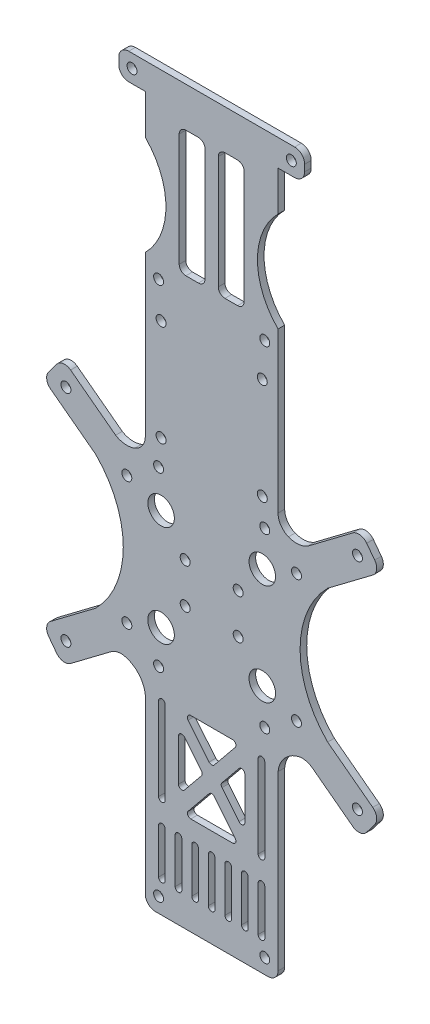
SolidWorks part; units mm, degrees
material "Thornel Mat VMA"
ref_plane "Alzado" through (0, 0, 0) normal (0, 0, 1) x (1, 0, 0)
ref_plane "Planta" through (0, 0, 0) normal (0, 1, 0) x (1, 0, 0)
ref_plane "Vista lateral" through (0, 0, 0) normal (1, 0, 0) x (0, 0, -1)
sketch "Croquis1" plane through (0, 0, 0) normal (0, 0, 1) x (1, 0, 0)
  line L0 (0, 0) -> (0, 130.25) construction
  line L1 (-15.25, 15.25) -> (15.25, 15.25) construction
  line L2 (-15.25, 15.25) -> (-15.25, -15.25) construction
  line L3 (-15.25, -15.25) -> (15.25, -15.25) construction
  line L4 (15.25, 15.25) -> (15.25, -15.25) construction
  line L5 (-15.25, 15.25) -> (15.25, -15.25) construction
  line L6 (-15.25, -15.25) -> (15.25, 15.25) construction
  line L7 (0, 0) -> (0, -90.25) construction
  line L8 (20, 130.25) -> (-20, 130.25)
  line L9 (-20, 130.25) -> (-20, 30.25)
  line L10 (20, -90.25) -> (-20, -90.25)
  line L11 (-20, -90.25) -> (-20, -35.25)
  line L12 (0, 0) -> (-127.7817, 96.2904) construction
  line L13 (0, 0) -> (-127.7817, -96.2904) construction
  line L14 (0, 0) -> (-160, 0) construction
  line L15 (-47.9181, 36.1089) -> (-50.9272, 32.1157)
  line L16 (-47.9181, 36.1089) -> (-44.9091, 40.1021)
  line L17 (-44.9091, 40.1021) -> (-28.9363, 28.0658)
  line L18 (-50.9272, 32.1157) -> (-34.9545, 20.0794)
  line L19 (-47.9181, -36.1089) -> (-50.9272, -32.1157)
  line L20 (-47.9181, -36.1089) -> (-44.9091, -40.1021)
  line L21 (-50.9272, -32.1157) -> (-34.9545, -20.0794)
  line L22 (-44.9091, -40.1021) -> (-28.9363, -28.0658)
  line L23 (20, -90.25) -> (20, -35.25)
  line L24 (44.9091, -40.1021) -> (28.9363, -28.0658)
  line L25 (47.9181, -36.1089) -> (44.9091, -40.1021)
  line L26 (47.9181, -36.1089) -> (50.9272, -32.1157)
  line L27 (50.9272, -32.1157) -> (34.9545, -20.0794)
  line L28 (50.9272, 32.1157) -> (34.9545, 20.0794)
  line L29 (47.9181, 36.1089) -> (50.9272, 32.1157)
  line L30 (47.9181, 36.1089) -> (44.9091, 40.1021)
  line L31 (44.9091, 40.1021) -> (28.9363, 28.0658)
  line L32 (20, 130.25) -> (20, 30.25)
  line L33 (-11, -67.25) -> (-11, -80.75)
  line L35 (-16, -67.25) -> (-16, -80.75)
  line L37 (-14, -67.25) -> (-14, -80.75)
  line L38 (-9, -67.25) -> (-9, -80.75)
  line L39 (-6, -67.25) -> (-6, -80.75)
  line L40 (-4, -67.25) -> (-4, -80.75)
  line L41 (-1, -67.25) -> (-1, -80.75)
  line L42 (1, -67.25) -> (1, -80.75)
  line L43 (4, -67.25) -> (4, -80.75)
  line L44 (6, -67.25) -> (6, -80.75)
  line L45 (9, -67.25) -> (9, -80.75)
  line L46 (11, -67.25) -> (11, -80.75)
  line L47 (14, -67.25) -> (14, -80.75)
  line L48 (16, -67.25) -> (16, -80.75)
  line L91 (-11, 62.75) -> (-11, 49.25) [skipped]
  line L92 (-9, 62.75) -> (-9, 49.25) [skipped]
  line L93 (-6, 62.75) -> (-6, 49.25) [skipped]
  line L94 (-4, 62.75) -> (-4, 49.25) [skipped]
  line L95 (-1, 62.75) -> (-1, 49.25) [skipped]
  line L96 (1, 62.75) -> (1, 49.25) [skipped]
  line L97 (4, 62.75) -> (4, 49.25) [skipped]
  line L98 (6, 62.75) -> (6, 49.25) [skipped]
  line L99 (9, 62.75) -> (9, 49.25) [skipped]
  line L100 (11, 62.75) -> (11, 49.25) [skipped]
  line L101 (14, 62.75) -> (14, 49.25) [skipped]
  line L102 (16, 62.75) -> (16, 49.25) [skipped]
  line L103 (-16, 62.75) -> (-16, 49.25) [skipped]
  line L104 (-14, 62.75) -> (-14, 49.25) [skipped]
  line L105 (14, -34.75) -> (14, -59.75)
  line L107 (-16, -34.75) -> (-16, -59.75)
  line L109 (-14, -34.75) -> (-14, -59.75)
  line L110 (16, -34.75) -> (16, -59.75)
  line L111 (-20, 130.25) -> (-10, 130.25) construction
  circle A0 centre (-15.25, 15.25) radius 4
  circle A1 centre (-15.25, -15.25) radius 4
  circle A2 centre (0, 0) radius 160 construction
  circle A4 centre (-127.7817, 96.2904) radius 90 construction
  circle A5 centre (-127.7817, -96.2904) radius 90 construction
  arc A6 (-28.9363, 28.0658) -> (-20, 30.25) centre (-25.5603, 33.6261) ccw
  arc A7 (-34.9545, 20.0794) -> (-34.9545, -20.0794) centre (-55.0339, 0) cw
  arc A8 (-28.9363, -28.0658) -> (-20, -35.25) centre (-28.0603, -36.1261) cw
  circle A9 centre (15.25, -15.25) radius 4
  arc A10 (28.9363, -28.0658) -> (20, -35.25) centre (28.0603, -36.1261) ccw
  circle A11 centre (15.25, 15.25) radius 4
  arc A12 (34.9545, 20.0794) -> (34.9545, -20.0794) centre (55.0339, 0) ccw
  arc A13 (28.9363, 28.0658) -> (20, 30.25) centre (25.5603, 33.6261) cw
  circle A14 centre (-43.925, 33.0998) radius 1.5
  circle A15 centre (-43.925, -33.0998) radius 1.5
  circle A16 centre (43.925, -33.0998) radius 1.5
  circle A17 centre (43.925, 33.0998) radius 1.5
  circle A23 centre (-7.9864, 6.0182) radius 1.5
  circle A24 centre (-25.5603, 19.2611) radius 1.5
  circle A25 centre (-25.5603, -19.2611) radius 1.5
  circle A26 centre (-7.9864, -6.0182) radius 1.5
  circle A27 centre (25.5603, -19.2611) radius 1.5
  circle A28 centre (7.9864, -6.0182) radius 1.5
  circle A29 centre (7.9864, 6.0182) radius 1.5
  circle A30 centre (25.5603, 19.2611) radius 1.5
  circle A31 centre (-16, -85.75) radius 1.5
  circle A32 centre (-16, -25.75) radius 1.5
  circle A33 centre (-16, 26.25) radius 1.5
  circle A34 centre (-16, 75.25) radius 1.5
  circle A35 centre (16, -85.75) radius 1.5
  circle A36 centre (16, -25.75) radius 1.5
  circle A37 centre (16, 26.25) radius 1.5
  circle A38 centre (16, 75.25) radius 1.5
  arc A39 (-16, -67.25) -> (-14, -67.25) centre (-15, -67.25) cw
  arc A40 (-16, -80.75) -> (-14, -80.75) centre (-15, -80.75) ccw
  arc A41 (-11, -80.75) -> (-9, -80.75) centre (-10, -80.75) ccw
  arc A42 (-11, -67.25) -> (-9, -67.25) centre (-10, -67.25) cw
  arc A43 (-6, -80.75) -> (-4, -80.75) centre (-5, -80.75) ccw
  arc A44 (-6, -67.25) -> (-4, -67.25) centre (-5, -67.25) cw
  arc A45 (-1, -80.75) -> (1, -80.75) centre (0, -80.75) ccw
  arc A46 (-1, -67.25) -> (1, -67.25) centre (0, -67.25) cw
  arc A47 (4, -80.75) -> (6, -80.75) centre (5, -80.75) ccw
  arc A48 (4, -67.25) -> (6, -67.25) centre (5, -67.25) cw
  arc A49 (9, -80.75) -> (11, -80.75) centre (10, -80.75) ccw
  arc A50 (9, -67.25) -> (11, -67.25) centre (10, -67.25) cw
  arc A51 (14, -80.75) -> (16, -80.75) centre (15, -80.75) ccw
  arc A52 (14, -67.25) -> (16, -67.25) centre (15, -67.25) cw
  arc A95 (-11, 49.25) -> (-9, 49.25) centre (-10, 49.25) ccw [skipped]
  arc A96 (-11, 62.75) -> (-9, 62.75) centre (-10, 62.75) cw [skipped]
  arc A97 (-6, 49.25) -> (-4, 49.25) centre (-5, 49.25) ccw [skipped]
  arc A98 (-6, 62.75) -> (-4, 62.75) centre (-5, 62.75) cw [skipped]
  arc A99 (-1, 49.25) -> (1, 49.25) centre (0, 49.25) ccw [skipped]
  arc A100 (-1, 62.75) -> (1, 62.75) centre (0, 62.75) cw [skipped]
  arc A101 (4, 49.25) -> (6, 49.25) centre (5, 49.25) ccw [skipped]
  arc A102 (4, 62.75) -> (6, 62.75) centre (5, 62.75) cw [skipped]
  arc A103 (9, 49.25) -> (11, 49.25) centre (10, 49.25) ccw [skipped]
  arc A104 (9, 62.75) -> (11, 62.75) centre (10, 62.75) cw [skipped]
  arc A105 (14, 49.25) -> (16, 49.25) centre (15, 49.25) ccw [skipped]
  arc A106 (14, 62.75) -> (16, 62.75) centre (15, 62.75) cw [skipped]
  arc A107 (-16, 49.25) -> (-14, 49.25) centre (-15, 49.25) ccw [skipped]
  arc A108 (-16, 62.75) -> (-14, 62.75) centre (-15, 62.75) cw [skipped]
  circle A109 centre (-15.25, 64.75) radius 1.5
  circle A110 centre (15.25, 64.75) radius 1.5
  circle A111 centre (15.25, 34.25) radius 1.5
  circle A112 centre (-15.25, 34.25) radius 1.5
  arc A113 (-16, -34.75) -> (-14, -34.75) centre (-15, -34.75) cw
  arc A114 (-16, -59.75) -> (-14, -59.75) centre (-15, -59.75) ccw
  arc A115 (16, -59.75) -> (14, -59.75) centre (15, -59.75) cw
  arc A116 (16, -34.75) -> (14, -34.75) centre (15, -34.75) ccw
  point P1 (0, 0)
  dimension "D2" = 130.25
  dimension "D8" = 30.5
  dimension "D9" = 180
  dimension "D10" = 320
  dimension "D13" = 180
  dimension "D20" = 5
  dimension "D21" = 5
  dimension "D22" = 8
  dimension "D23" = 8
  dimension "D24" = 9.5
  dimension "D25" = 8
  dimension "D26" = 4.75
  dimension "D28" = 10
  dimension "D29" = 16
  dimension "D31" = 16
  dimension "D33" = 3
  dimension "D34" = 16
  dimension "D36" = 4.75
  dimension "D41" = 8.1078
  dimension "D27" = 6.505
  dimension "D32" = 20
  dimension "D1" = 30.5
  dimension "D4" = 20
  dimension "D5" = 13.5
  dimension "D6" = 20
  dimension "D7" = 10
  dimension "D11" = 37
  dimension "D12" = 37
  dimension "D14" = 60
  dimension "D15" = 5
  dimension "D16" = 5
  dimension "D17" = 20
  dimension "D18" = 60
  dimension "D19" = 5
  dimension "D30" = 4.5
  dimension "D35" = 11
  dimension "D37" = 5
  dimension "D38" = 2
  dimension "D39" = 4
  dimension "D40" = 55
  dimension "D42" = 25
  dimension "D43" = 9
  dimension "D46" = 55
  dimension "D47" = 4
  dimension "D49" = 2
  dimension "D44" = 7
  dimension "D45" = 2
extrude "Saliente-Extruir1" add sketch "Croquis1" along normal blind 2
sketch "Croquis2" plane through (0, 0, 2) normal (0, 0, 1) x (1, 0, 0)
  line L0 (-28.9363, 28.0658) -> (-44.9091, 40.1021)
  line L1 (-44.9091, 40.1021) -> (-50.9272, 32.1157)
  line L2 (-50.9272, 32.1157) -> (-34.9545, 20.0794)
  circle A0 centre (-43.925, 33.0998) radius 1.5
  circle A1 centre (-25.5603, 19.2611) radius 1.5
  circle A2 centre (-15.25, 15.25) radius 4
  circle A3 centre (-7.9864, 6.0182) radius 1.5
  circle A4 centre (-16, 26.25) radius 1.5
  circle A5 centre (0, 0) radius 10
fillet "Redondeo2" radius 3 10 edges at (50.9272, -32.1157, 1) (44.9091, -40.1021, 1) (50.9272, 32.1157, 1) (44.9091, 40.1021, 1) (-44.9091, 40.1021, 1) (-50.9272, 32.1157, 1) (-50.9272, -32.1157, 1) (-44.9091, -40.1021, 1) (20, -90.25, 1) (-20, -90.25, 1)
fillet "Redondeo3" radius 5 4 edges at (20, 30.25, 1) (-20, 30.25, 1) (28.9363, -28.0658, 1) (-28.9363, -28.0658, 1)
sketch "Croquis3" plane through (0, 0, 2) normal (0, 0, 1) x (1, 0, 0)
  line L0 (-20, 130.25) -> (-20, 32.2293) construction
  line L1 (-17, 79.75) -> (17, 79.75)
  line L2 (-20, 76.75) -> (-20, -87.25)
  line L3 (-17, -90.25) -> (17, -90.25)
  line L4 (20, 76.75) -> (20, -87.25)
  line L5 (-17, -90.25) -> (17, -90.25) construction
  circle A2 centre (-16, 75.25) radius 1.5
  circle A3 centre (16, 75.25) radius 1.5
  circle A4 centre (-16, 26.25) radius 1.5
  circle A5 centre (16, 26.25) radius 1.5
  circle A6 centre (-16, -25.75) radius 1.5
  circle A7 centre (16, -25.75) radius 1.5
  circle A8 centre (-16, -85.75) radius 1.5
  circle A9 centre (16, -85.75) radius 1.5
  arc A11 (-17, 79.75) -> (-20, 76.75) centre (-17, 76.75) ccw
  arc A12 (17, 79.75) -> (20, 76.75) centre (17, 76.75) cw
  arc A13 (17, -90.25) -> (20, -87.25) centre (17, -87.25) ccw
  arc A14 (-20, -87.25) -> (-17, -90.25) centre (-17, -87.25) ccw
  point P32 (20, 79.75)
  point P35 (-20, 79.75)
  point P38 (20, -90.25)
  dimension "D2" = 3
  dimension "D1" = 34
  dimension "D3" = 4.5
  dimension "D4" = 0
sketch "Croquis4" plane through (0, 0, 2) normal (0, 0, 1) x (1, 0, 0)
  line L0 (20, 32.2293) -> (20, 130.25) construction
  line L1 (-20, 130.25) -> (20, 130.25)
  line L2 (-20, 130.25) -> (-20, 70.25)
  line L3 (-20, 70.25) -> (20, 70.25)
  line L4 (20, 130.25) -> (20, 70.25)
  circle A0 centre (-16, 75.25) radius 1.5 construction
  circle A2 centre (-16, 75.25) radius 1.5
  circle A3 centre (16, 75.25) radius 1.5
  dimension "D1" = 5
sketch "Croquis5" plane through (0, 0, 2) normal (0, 0, 1) x (1, 0, 0)
  line L0 (-28, 122.25) -> (-20, 130.25) construction
  line L1 (-20, 130.25) -> (-25, 130.25)
  line L2 (-20, 130.25) -> (-20, 122.25)
  line L3 (-20, 122.25) -> (-25, 122.25)
  line L4 (-28, 127.25) -> (-28, 125.25)
  line L5 (0, 130.25) -> (0, 122.25) construction
  line L6 (20, 130.25) -> (-20, 130.25) construction
  line L7 (28, 122.25) -> (20, 130.25) construction
  line L8 (28, 127.25) -> (28, 125.25)
  line L9 (20, 122.25) -> (25, 122.25)
  line L10 (20, 130.25) -> (20, 122.25)
  line L11 (20, 130.25) -> (25, 130.25)
  circle A0 centre (-24, 126.25) radius 1.5
  arc A1 (-25, 122.25) -> (-28, 125.25) centre (-25, 125.25) cw
  arc A2 (-25, 130.25) -> (-28, 127.25) centre (-25, 127.25) ccw
  arc A3 (25, 130.25) -> (28, 127.25) centre (25, 127.25) cw
  arc A4 (25, 122.25) -> (28, 125.25) centre (25, 125.25) ccw
  circle A5 centre (24, 126.25) radius 1.5
  point P12 (-28, 130.25)
  point P29 (28, 130.25)
  dimension "D3" = 3
  dimension "D4" = 3
  dimension "D1" = 8
  dimension "D2" = 8
extrude "Saliente-Extruir2" add sketch "Croquis5" against normal up to vertex (2 mm away)
sketch "Croquis6" plane through (0, 0, 2) normal (0, 0, 1) x (1, 0, 0)
  line L0 (-20, 110.25) -> (-20, 80.25)
  line L1 (-20, 122.25) -> (-20, 32.2293) construction
  line L2 (25, 130.25) -> (-25, 130.25) construction
  line L3 (0, 130.25) -> (0, 81.7794) construction
  line L4 (20, 110.25) -> (20, 80.25)
  line L5 (-14, -59.75) -> (-14, -34.75) construction
  line L6 (-11, -33.75) -> (11, -33.75) construction
  line L7 (-11, -33.75) -> (-11, -60.75) construction
  line L8 (-11, -60.75) -> (11, -60.75) construction
  line L9 (11, -33.75) -> (11, -60.75) construction
  line L10 (14, -34.75) -> (14, -59.75) construction
  line L11 (-11, -33.75) -> (11, -60.75) construction
  line L12 (11, -33.75) -> (-11, -60.75) construction
  line L19 (-8.2248, -40.3222) -> (-3.0946, -46.6183)
  line L20 (-3.0946, -47.8817) -> (-8.2248, -54.1778)
  line L21 (-10, -53.5462) -> (-10, -40.9538)
  line L22 (10, -53.5462) -> (10, -40.9538)
  line L23 (3.0946, -47.8817) -> (8.2248, -54.1778)
  line L24 (8.2248, -40.3222) -> (3.0946, -46.6183)
  line L25 (-2.5799, -47.25) -> (2.5799, -47.25) construction
  line L26 (-7.0906, -35.3817) -> (-0.7752, -43.1324)
  line L27 (0.7752, -43.1324) -> (7.0906, -35.3817)
  line L28 (6.3154, -33.75) -> (-6.3154, -33.75)
  line L29 (0.7752, -51.3676) -> (7.0906, -59.1183)
  line L30 (-7.0906, -59.1183) -> (-0.7752, -51.3676)
  line L31 (6.3154, -60.75) -> (-6.3154, -60.75)
  line L33 (13.7868, 95.25) -> (-13.7868, 95.25) construction
  line L39 (2, 116.25) -> (2, 82.25)
  line L40 (-7.7868, 118.25) -> (-4, 118.25)
  line L41 (-9.7868, 116.25) -> (-9.7868, 82.25)
  line L42 (-7.7868, 80.25) -> (-4, 80.25)
  line L43 (-2, 116.25) -> (-2, 82.25)
  line L44 (7.7868, 80.25) -> (4, 80.25)
  line L45 (9.7868, 116.25) -> (9.7868, 82.25)
  line L46 (7.7868, 118.25) -> (4, 118.25)
  arc A0 (-20, 110.25) -> (-20, 80.25) centre (-35, 95.25) cw
  arc A1 (20, 110.25) -> (20, 80.25) centre (35, 95.25) ccw
  arc A2 (7.0906, -35.3817) -> (6.3154, -33.75) centre (6.3154, -34.75) ccw
  arc A3 (-7.0906, -35.3817) -> (-6.3154, -33.75) centre (-6.3154, -34.75) cw
  arc A4 (-0.7752, -43.1324) -> (0.7752, -43.1324) centre (0, -42.5007) ccw
  arc A5 (-3.0946, -46.6183) -> (-3.0946, -47.8817) centre (-3.8698, -47.25) cw
  arc A6 (-8.2248, -54.1778) -> (-10, -53.5462) centre (-9, -53.5462) cw
  arc A7 (-8.2248, -40.3222) -> (-10, -40.9538) centre (-9, -40.9538) ccw
  arc A8 (10, -53.5462) -> (8.2248, -54.1778) centre (9, -53.5462) cw
  arc A9 (3.0946, -47.8817) -> (3.0946, -46.6183) centre (3.8698, -47.25) cw
  arc A10 (10, -40.9538) -> (8.2248, -40.3222) centre (9, -40.9538) ccw
  arc A11 (7.0906, -59.1183) -> (6.3154, -60.75) centre (6.3154, -59.75) cw
  arc A12 (-0.7752, -51.3676) -> (0.7752, -51.3676) centre (0, -51.9993) cw
  arc A13 (-7.0906, -59.1183) -> (-6.3154, -60.75) centre (-6.3154, -59.75) ccw
  arc A20 (-4, 80.25) -> (-2, 82.25) centre (-4, 82.25) ccw
  arc A21 (-9.7868, 82.25) -> (-7.7868, 80.25) centre (-7.7868, 82.25) ccw
  arc A22 (-4, 118.25) -> (-2, 116.25) centre (-4, 116.25) cw
  arc A23 (-7.7868, 118.25) -> (-9.7868, 116.25) centre (-7.7868, 116.25) ccw
  arc A24 (7.7868, 118.25) -> (9.7868, 116.25) centre (7.7868, 116.25) cw
  arc A25 (4, 118.25) -> (2, 116.25) centre (4, 116.25) ccw
  arc A26 (9.7868, 82.25) -> (7.7868, 80.25) centre (7.7868, 82.25) cw
  arc A27 (4, 80.25) -> (2, 82.25) centre (4, 82.25) cw
  point P41 (-10, -56.3565)
  point P44 (-10, -38.1435)
  point P47 (10, -56.3565)
  point P53 (10, -38.1435)
  point P73 (-9.7868, 80.25)
  point P78 (-9.7868, 118.25)
  dimension "D12" = 1
  dimension "D13" = 1
  dimension "D16" = 12
  dimension "D18" = 2
  dimension "D1" = 30
  dimension "D2" = 20
  dimension "D3" = 3
  dimension "D4" = 3
  dimension "D5" = 1
  dimension "D6" = 27
  dimension "D7" = 2
  dimension "D8" = 2
  dimension "D9" = 0
  dimension "D10" = 2
  dimension "D11" = 2
  dimension "D14" = 4
  dimension "D15" = 2
  dimension "D17" = 38
extrude "Cortar-Extruir1" cut sketch "Croquis6" against normal up to vertex (2 mm away)
sketch "Croquis_Soporte_Antennas" plane through (0, 0, 2) normal (0, 0, 1) x (1, 0, 0)
  line L0 (-17, -90.25) -> (17, -90.25)
  line L1 (-17, -90.25) -> (17, -90.25) construction
  line L2 (-20, -87.25) -> (-20, -81.75)
  line L3 (-20, -35.25) -> (-20, -87.25) construction
  line L4 (-20, -81.75) -> (20, -81.75)
  line L5 (20, -87.25) -> (20, -35.25) construction
  line L6 (20, -81.75) -> (20, -87.25)
  arc A0 (-17, -90.25) -> (-20, -87.25) centre (-17, -87.25) cw
  arc A1 (17, -90.25) -> (20, -87.25) centre (17, -87.25) ccw
  circle A2 centre (-16, -85.75) radius 2.5
  circle A3 centre (16, -85.75) radius 2.5
